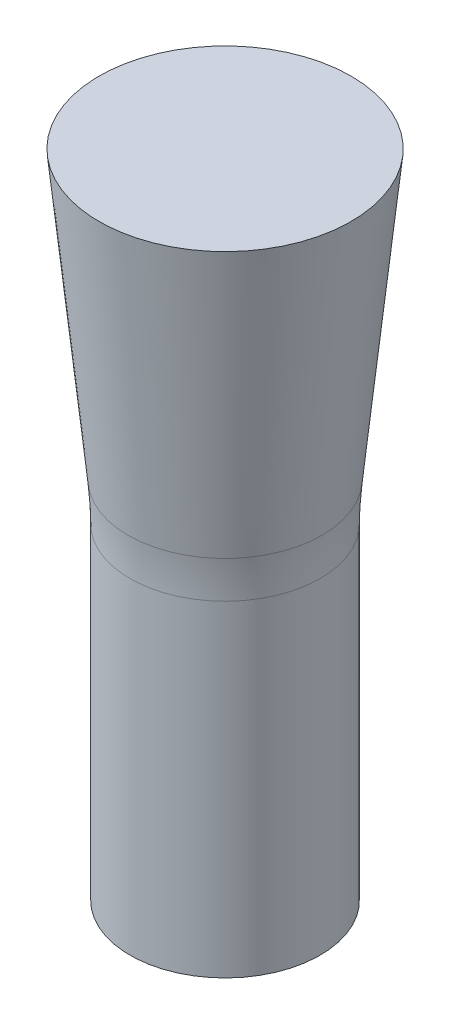
SolidWorks part; units mm, degrees
ref_plane "Front Plane" through (0, 0, 0) normal (0, 0, 1) x (1, 0, 0)
ref_plane "Top Plane" through (0, 0, 0) normal (0, 1, 0) x (1, 0, 0)
ref_plane "Right Plane" through (0, 0, 0) normal (1, 0, 0) x (0, 0, -1)
sketch "Sketch4" plane through (0, 0, 0) normal (0, 0, 1) x (1, 0, 0)
  line L0 (0, 0) -> (0, 12.05)
  line L4 (2.49, 8.545) -> (2.49, 0)
  line L5 (2.49, 0) -> (0, 0)
  line L6 (2.5409, 9.5524) -> (3.3, 17.05)
  line L7 (3.3, 17.05) -> (0, 17.05)
  line L8 (0, 17.05) -> (0, 12.05)
  arc A0 (2.49, 8.545) -> (2.5409, 9.5524) centre (12.49, 8.545) cw
  point P5 (2.49, 9.05)
  dimension "D5" = 10
  dimension "D1" = 9.05
  dimension "D2" = 2.49
  dimension "D3" = 3.3
  dimension "D4" = 8
revolve "Revolve1" add sketch "Sketch4" angle 360 about L0
